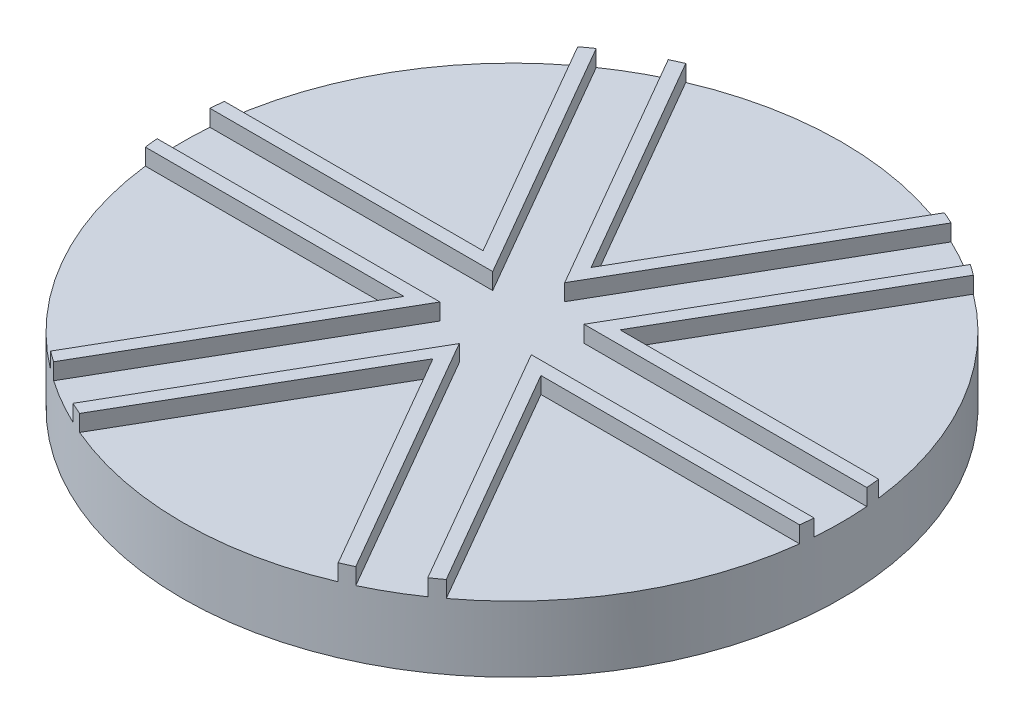
SolidWorks part; units mm, degrees
ref_plane "Front Plane" through (0, 0, 0) normal (0, 0, 1) x (1, 0, 0)
ref_plane "Top Plane" through (0, 0, 0) normal (0, 1, 0) x (1, 0, 0)
ref_plane "Right Plane" through (0, 0, 0) normal (1, 0, 0) x (0, 0, -1)
sketch "Sketch1" plane through (0, 0, 0) normal (0, 1, 0) x (1, 0, 0)
  circle A0 centre (0, 0) radius 127
  dimension "D1" = 254
extrude "Boss-Extrude1" add sketch "Sketch1" along normal blind 25.4
sketch "Sketch2" plane through (0, 25.4, 0) normal (0, 1, 0) x (1, 0, 0)
  line L0 (-127, 0) -> (127, 0) construction
  line L1 (63.5, 109.9852) -> (-63.5, -109.9852) construction
  line L2 (63.5, -109.9852) -> (-63.5, 109.9852) construction
  line L3 (74.1802, -103.0839) -> (21.997, -12.7) construction
  line L4 (-126.3634, -12.7) -> (-21.997, -12.7) construction
  line L5 (52.1832, 115.7839) -> (0, 25.4) construction
  line L6 (52.1832, -115.7839) -> (0, -25.4) construction
  line L7 (-126.3634, 12.7) -> (-21.997, 12.7) construction
  line L8 (74.1802, 103.0839) -> (21.997, 12.7) construction
  line L9 (-21.997, -12.7) -> (-74.1802, -103.0839) construction
  line L10 (52.5015, 116.3352) -> (-74.4985, -103.6352) construction
  line L11 (-21.997, 12.7) -> (-74.1802, 103.0839) construction
  line L12 (52.5015, -116.3352) -> (-74.4985, 103.6352) construction
  line L13 (21.997, 12.7) -> (126.3634, 12.7) construction
  line L14 (-127, 12.7) -> (127, 12.7) construction
  line L15 (0, 25.4) -> (-52.1832, 115.7839) construction
  line L16 (74.4985, -103.6352) -> (-52.5015, 116.3352) construction
  line L17 (21.997, -12.7) -> (126.3634, -12.7) construction
  line L18 (-127, -12.7) -> (127, -12.7) construction
  line L19 (0, -25.4) -> (-52.1832, -115.7839) construction
  line L20 (74.4985, 103.6352) -> (-52.5015, -116.3352) construction
  line L21 (-126.5929, 10.16) -> (-17.5976, 10.16)
  line L22 (-17.5976, 10.16) -> (-72.0953, 104.5527)
  line L23 (-126.0823, -15.24) -> (-26.3965, -15.24)
  line L24 (-26.3965, -15.24) -> (-76.2394, -101.5705)
  line L25 (54.4977, -114.7127) -> (0, -20.32)
  line L26 (0, -20.32) -> (-54.4977, -114.7127)
  line L27 (76.2394, -101.5705) -> (26.3965, -15.24)
  line L28 (26.3965, -15.24) -> (126.0823, -15.24)
  line L29 (72.0953, 104.5527) -> (17.5976, 10.16)
  line L30 (17.5976, 10.16) -> (126.5929, 10.16)
  line L31 (49.8429, 116.8105) -> (0, 30.48)
  line L32 (0, 30.48) -> (-49.8429, 116.8105)
  line L33 (-126.0823, 15.24) -> (-26.3965, 15.24)
  line L34 (-26.3965, 15.24) -> (-76.2394, 101.5705)
  line L35 (-126.5929, -10.16) -> (-17.5976, -10.16)
  line L36 (-17.5976, -10.16) -> (-72.0953, -104.5527)
  line L37 (49.8429, -116.8105) -> (0, -30.48)
  line L38 (0, -30.48) -> (-49.8429, -116.8105)
  line L39 (72.0953, -104.5527) -> (17.5976, -10.16)
  line L40 (17.5976, -10.16) -> (126.5929, -10.16)
  line L41 (76.2394, 101.5705) -> (26.3965, 15.24)
  line L42 (26.3965, 15.24) -> (126.0823, 15.24)
  line L43 (54.4977, 114.7127) -> (0, 20.32)
  line L44 (0, 20.32) -> (-54.4977, 114.7127)
  line L45 (26.3965, 15.24) -> (127, 15.24) construction
  line L46 (21.997, 12.7) -> (127, 12.7) construction
  line L47 (17.5976, 10.16) -> (127, 10.16) construction
  line L48 (17.5976, -10.16) -> (127, -10.16) construction
  line L49 (21.997, -12.7) -> (127, -12.7) construction
  line L50 (26.3965, -15.24) -> (127, -15.24) construction
  line L51 (50.3018, 117.6052) -> (0, 30.48) construction
  line L52 (52.5015, 116.3352) -> (0, 25.4) construction
  line L53 (54.7012, 115.0652) -> (0, 20.32) construction
  line L54 (72.2988, 104.9052) -> (17.5976, 10.16) construction
  line L55 (74.4985, 103.6352) -> (21.997, 12.7) construction
  line L56 (76.6982, 102.3652) -> (26.3965, 15.24) construction
  line L57 (0, 25.4) -> (-52.5015, 116.3352) construction
  line L58 (0, 30.48) -> (-50.3018, 117.6052) construction
  line L59 (0, 20.32) -> (-54.7012, 115.0652) construction
  line L60 (-26.3965, 15.24) -> (-76.6982, 102.3652) construction
  line L61 (-21.997, 12.7) -> (-74.4985, 103.6352) construction
  line L62 (-17.5976, 10.16) -> (-72.2988, 104.9052) construction
  line L63 (63.5, 109.9852) -> (-63.5, -109.9852) construction
  line L64 (-127, 15.24) -> (-26.3965, 15.24) construction
  line L65 (-127, 12.7) -> (-21.997, 12.7) construction
  line L66 (-127, 10.16) -> (-17.5976, 10.16) construction
  line L67 (-127, -10.16) -> (-17.5976, -10.16) construction
  line L68 (-127, -12.7) -> (-21.997, -12.7) construction
  line L69 (-127, -15.24) -> (-26.3965, -15.24) construction
  line L70 (-26.3965, -15.24) -> (-76.6982, -102.3652) construction
  line L71 (-21.997, -12.7) -> (-74.4985, -103.6352) construction
  line L72 (-17.5976, -10.16) -> (-72.2988, -104.9052) construction
  line L73 (0, -20.32) -> (-54.7012, -115.0652) construction
  line L74 (0, -25.4) -> (-52.5015, -116.3352) construction
  line L75 (0, -30.48) -> (-50.3018, -117.6052) construction
  line L76 (50.3018, -117.6052) -> (0, -30.48) construction
  line L77 (52.5015, -116.3352) -> (0, -25.4) construction
  line L78 (54.7012, -115.0652) -> (0, -20.32) construction
  line L79 (72.2988, -104.9052) -> (17.5976, -10.16) construction
  line L80 (74.4985, -103.6352) -> (21.997, -12.7) construction
  line L81 (76.6982, -102.3652) -> (26.3965, -15.24) construction
  circle A0 centre (0, 0) radius 127 construction
  arc A1 (126.5929, 10.16) -> (126.0823, 15.24) centre (0, 0) ccw
  arc A2 (76.2394, 101.5705) -> (72.0953, 104.5527) centre (0, 0) ccw
  arc A3 (54.4977, 114.7127) -> (49.8429, 116.8105) centre (0, 0) ccw
  arc A4 (-49.8429, 116.8105) -> (-54.4977, 114.7127) centre (0, 0) ccw
  arc A5 (-72.0953, 104.5527) -> (-76.2394, 101.5705) centre (0, 0) ccw
  arc A6 (-126.0823, 15.24) -> (-126.5929, 10.16) centre (0, 0) ccw
  arc A7 (-126.5929, -10.16) -> (-126.0823, -15.24) centre (0, 0) ccw
  arc A8 (-76.2394, -101.5705) -> (-72.0953, -104.5527) centre (0, 0) ccw
  arc A9 (-54.4977, -114.7127) -> (-49.8429, -116.8105) centre (0, 0) ccw
  arc A10 (49.8429, -116.8105) -> (54.4977, -114.7127) centre (0, 0) ccw
  arc A11 (126.0823, -15.24) -> (126.5929, -10.16) centre (0, 0) ccw
  arc A12 (72.0953, -104.5527) -> (76.2394, -101.5705) centre (0, 0) ccw
  point P7 (0, 0)
  point P11 (0, 0)
  point P14 (0, 0)
  point P86 (63.5, 109.9852)
  dimension "D1" = 60
  dimension "D2" = 60
  dimension "D3" = 12.7
  dimension "D4" = 12.7
  dimension "D5" = 2.54
  dimension "D6" = 2.54
extrude "Boss-Extrude2" add sketch "Sketch2" along normal blind 6.35
